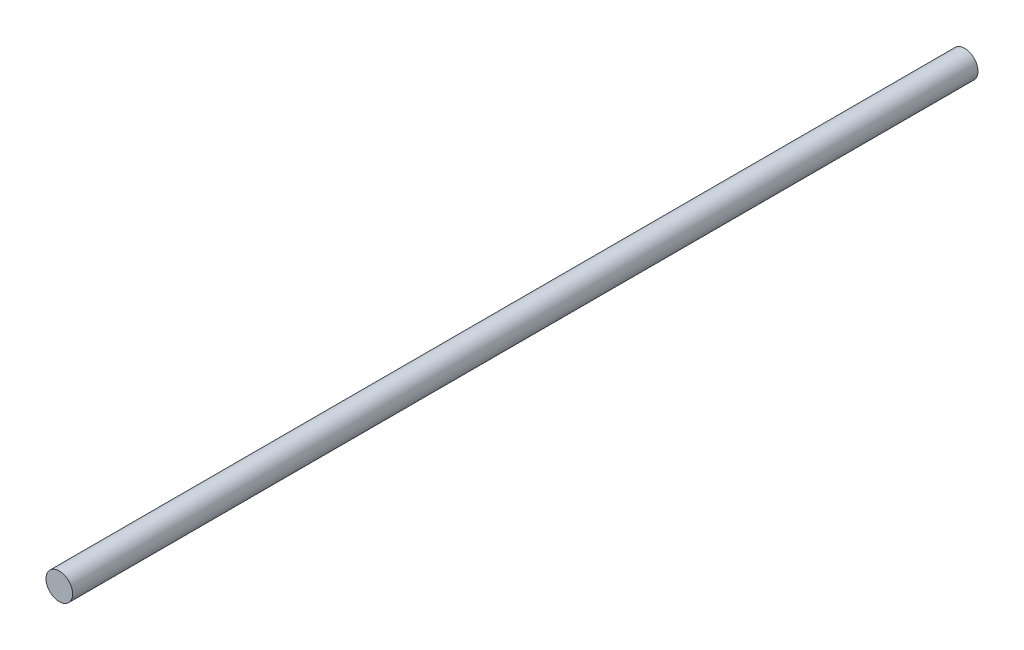
SolidWorks part; units mm, degrees
ref_plane "Front Plane" through (0, 0, 0) normal (0, 0, 1) x (1, 0, 0)
ref_plane "Top Plane" through (0, 0, 0) normal (0, 1, 0) x (1, 0, 0)
ref_plane "Right Plane" through (0, 0, 0) normal (1, 0, 0) x (0, 0, -1)
sketch "Sketch1" plane through (0, 0, 0) normal (0, 0, 1) x (1, 0, 0)
  circle A0 centre (0, 0) radius 2.5
  dimension "D1" = 5
extrude "Boss-Extrude1" add sketch "Sketch1" along normal blind 170
